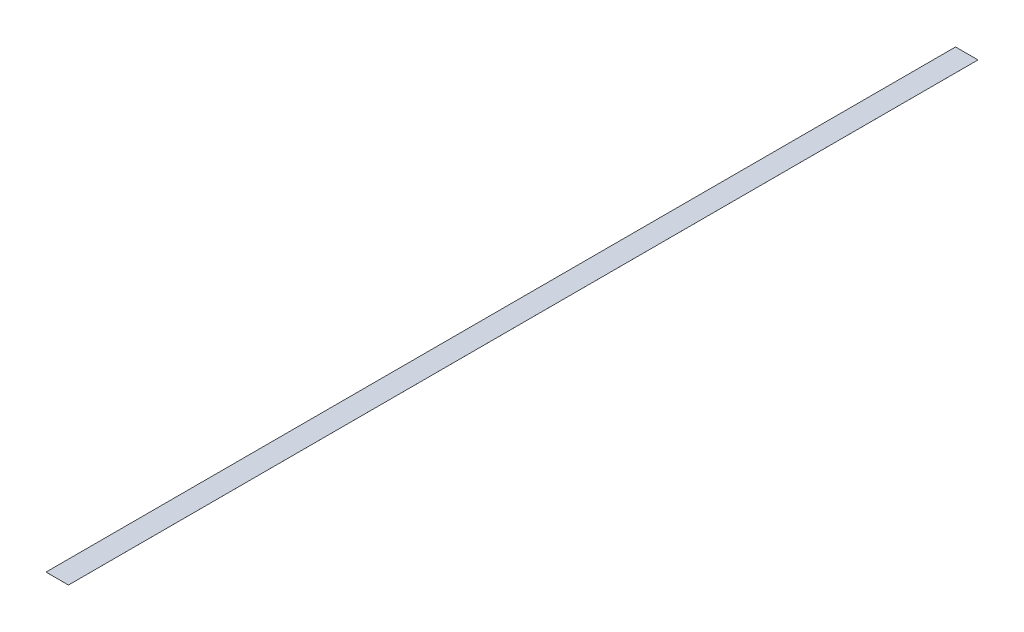
SolidWorks part; units mm, degrees
ref_plane "Plano frontal" through (0, 0, 0) normal (0, 0, 1) x (1, 0, 0)
ref_plane "Plano superior" through (0, 0, 0) normal (0, 1, 0) x (1, 0, 0)
ref_plane "Plano direito" through (0, 0, 0) normal (1, 0, 0) x (0, 0, -1)
sketch "Esboço1" plane through (0, 0, 0) normal (0, 1, 0) x (1, 0, 0)
  line L0 (-1093, 595.536) -> (-1073, 595.536)
  line L1 (0, 0) -> (18.9344, 0)
  line L2 (0, 0) -> (0, 766.8662)
  line L3 (0, 766.8662) -> (18.9344, 766.8662)
  line L4 (18.9344, 0) -> (18.9344, 766.8662)
  line L5 (-381.6968, 766.8662) -> (-362.7624, 766.8662)
  line L6 (-381.6968, 766.8662) -> (-381.6968, 345.536)
  line L7 (-381.6968, 345.536) -> (-362.7624, 345.536)
  line L8 (-362.7624, 766.8662) -> (-362.7624, 345.536)
  line L9 (-858.9344, 645.536) -> (-840, 645.536)
  line L10 (-858.9344, 645.536) -> (-858.9344, 345.536)
  line L11 (-858.9344, 345.536) -> (-840, 345.536)
  line L12 (-840, 645.536) -> (-840, 345.536)
  line L13 (-853.5858, 925.2213) -> (-1253.5858, 925.2213)
  line L14 (-853.5858, 925.2213) -> (-853.5858, 945.2213)
  line L15 (-853.5858, 945.2213) -> (-1253.5858, 945.2213)
  line L16 (-1253.5858, 925.2213) -> (-1253.5858, 945.2213)
  line L17 (-1093, 595.536) -> (-1093, 195.536)
  line L18 (-1093, 195.536) -> (-1073, 195.536)
  line L19 (-1073, 595.536) -> (-1073, 195.536)
  line L21 (-858.9344, 427.7897) -> (-1250.0103, 427.7897)
  line L23 (-858.9344, 407.7897) -> (-1250.0103, 407.7897)
  line L24 (-1250.0103, 427.7897) -> (-1250.0103, 407.7897)
  line L33 (-1439.6613, 239.7512) -> (-1560.0448, 239.7512)
  line L34 (-1439.6613, 239.7512) -> (-1439.6613, 219.7512)
  line L35 (-1439.6613, 219.7512) -> (-1560.0448, 219.7512)
  line L36 (-1560.0448, 239.7512) -> (-1560.0448, 219.7512)
  line L37 (-1627.2015, 576.144) -> (-1607.2015, 576.144)
  line L38 (-1627.2015, 576.144) -> (-1627.2015, 317.0654)
  line L39 (-1627.2015, 317.0654) -> (-1607.2015, 317.0654)
  line L40 (-1607.2015, 576.144) -> (-1607.2015, 317.0654)
  line L41 (-1627.2015, 769.6927) -> (-1607.2015, 769.6927)
  line L42 (-1627.2015, 769.6927) -> (-1627.2015, 1019.6927)
  line L43 (-1627.2015, 1019.6927) -> (-1607.2015, 1019.6927)
  line L44 (-1607.2015, 769.6927) -> (-1607.2015, 1019.6927)
  line L49 (526.2664, 269.0045) -> (545.2008, 269.0045)
  line L50 (526.2664, 269.0045) -> (526.2664, 1035.8707)
  line L51 (526.2664, 1035.8707) -> (545.2008, 1035.8707)
  line L52 (545.2008, 269.0045) -> (545.2008, 1035.8707)
  arc A6 (-381.6968, 766.8662) -> (18.9344, 766.8662) centre (-181.3812, 766.8662) cw
  arc A7 (-362.7624, 766.8662) -> (0, 766.8662) centre (-181.3812, 766.8662) cw
  arc A8 (-362.7624, 345.536) -> (-858.9344, 345.536) centre (-610.8484, 345.536) cw
  arc A9 (-381.6968, 345.536) -> (-840, 345.536) centre (-610.8484, 345.536) cw
  arc A10 (-840, 645.536) -> (-803.6955, 702.0415) centre (-777.8744, 645.536) cw
  arc A11 (-803.6955, 702.0415) -> (-853.5858, 945.2213) centre (-856.6336, 817.8884) ccw
  arc A12 (-858.9344, 645.536) -> (-814.4955, 717.9247) centre (-777.7563, 645.536) cw
  arc A13 (-814.4955, 717.9247) -> (-853.5858, 925.2213) centre (-864.2122, 815.8835) ccw
  arc A14 (-1093, 595.536) -> (-1188.5366, 677.9223) centre (-1176.2913, 595.536) ccw
  arc A15 (-1188.5366, 677.9223) -> (-1354.3411, 742.8189) centre (-1214.8489, 854.9525) cw
  arc A16 (-1354.3411, 742.8189) -> (-1253.5858, 945.2213) centre (-1257.3278, 820.805) cw
  arc A17 (-1073, 595.536) -> (-1188.5366, 698.0004) centre (-1176.2038, 595.536) ccw
  arc A18 (-1188.5366, 698.0004) -> (-1341.8208, 766.8662) centre (-1207.9995, 859.705) cw
  arc A19 (-1341.8208, 766.8662) -> (-1253.5858, 925.2213) centre (-1258.876, 824.4093) cw
  arc A22 (-1368.7558, 309.7722) -> (-1439.6613, 219.7512) centre (-1474.849, 320.402) cw
  arc A23 (-1388.5562, 309.7722) -> (-1439.6613, 239.7512) centre (-1477.6183, 321.1143) cw
  arc A24 (-1388.5562, 309.7722) -> (-1250.0103, 427.7897) centre (-1254.4723, 292.6965) cw
  arc A25 (-1607.2015, 317.0654) -> (-1560.0448, 239.7512) centre (-1520.2441, 317.0654) ccw
  arc A26 (-1627.2015, 317.0654) -> (-1560.0448, 219.7512) centre (-1523.1159, 317.0654) ccw
  arc A27 (-1368.7558, 309.7722) -> (-1250.0103, 407.7897) centre (-1259.9289, 298.8686) cw
extrude "Ressalto-extrusão5" add sketch "Esboço1" along normal blind 0.01 contours L52 L51 L50 L49
